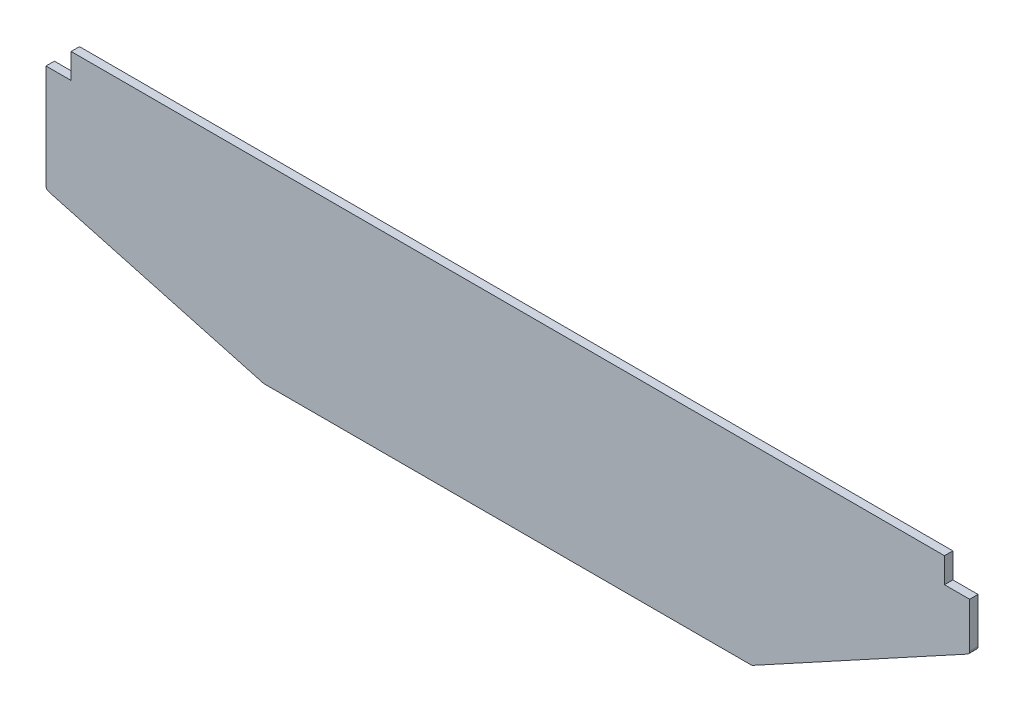
SolidWorks part; units mm, degrees
ref_plane "Front Plane" through (0, 0, 0) normal (0, 0, 1) x (1, 0, 0)
ref_plane "Top Plane" through (0, 0, 0) normal (0, 1, 0) x (1, 0, 0)
ref_plane "Right Plane" through (0, 0, 0) normal (1, 0, 0) x (0, 0, -1)
sketch "Sketch1" plane through (0, 0, 0) normal (0, 0, 1) x (1, 0, 0)
  line L0 (700, -53.2191) -> (700, 0) construction
  line L1 (535.6716, -144.6337) -> (698.4366, -55.8528) construction
  line L2 (165.4018, -145) -> (534.235, -145) construction
  line L3 (2.2106, -100.6029) -> (164.6124, -144.8943) construction
  line L4 (0, 0) -> (0, -97.7086) construction
  line L5 (700, -53.2191) -> (700, 0)
  line L10 (535.6716, -144.6337) -> (698.4366, -55.8528)
  line L11 (165.4018, -145) -> (534.235, -145)
  line L12 (2.2106, -100.6029) -> (164.6124, -144.8943)
  line L13 (0, 0) -> (0, -97.7086)
  line L14 (0, 0) -> (700, 0)
  arc A0 (698.4366, -55.8528) -> (700, -53.2191) centre (697, -53.2191) ccw construction
  arc A1 (534.235, -145) -> (535.6716, -144.6337) centre (534.235, -142) ccw construction
  arc A2 (164.6124, -144.8943) -> (165.4018, -145) centre (165.4018, -142) ccw construction
  arc A3 (0, -97.7086) -> (2.2106, -100.6029) centre (3, -97.7086) ccw construction
  arc A4 (698.4366, -55.8528) -> (700, -53.2191) centre (697, -53.2191) ccw
  arc A5 (534.235, -145) -> (535.6716, -144.6337) centre (534.235, -142) ccw
  arc A6 (164.6124, -144.8943) -> (165.4018, -145) centre (165.4018, -142) ccw
  arc A7 (0, -97.7086) -> (2.2106, -100.6029) centre (3, -97.7086) ccw
extrude "Boss-Extrude1" add sketch "Sketch1" along normal blind 6.35
sketch "Sketch2" plane through (0, 0, 6.35) normal (0, 0, 1) x (1, 0, 0)
  line L1 (0, 0) -> (19.05, 0)
  line L2 (0, 0) -> (0, -19.05)
  line L3 (0, -19.05) -> (19.05, -19.05)
  line L4 (19.05, 0) -> (19.05, -19.05)
  line L5 (680.95, 0) -> (700, 0)
  line L6 (680.95, 0) -> (680.95, -19.05)
  line L7 (680.95, -19.05) -> (700, -19.05)
  line L8 (700, 0) -> (700, -19.05)
  dimension "D1" = 19.05
extrude "Cut-Extrude1" cut sketch "Sketch2" against normal through all
